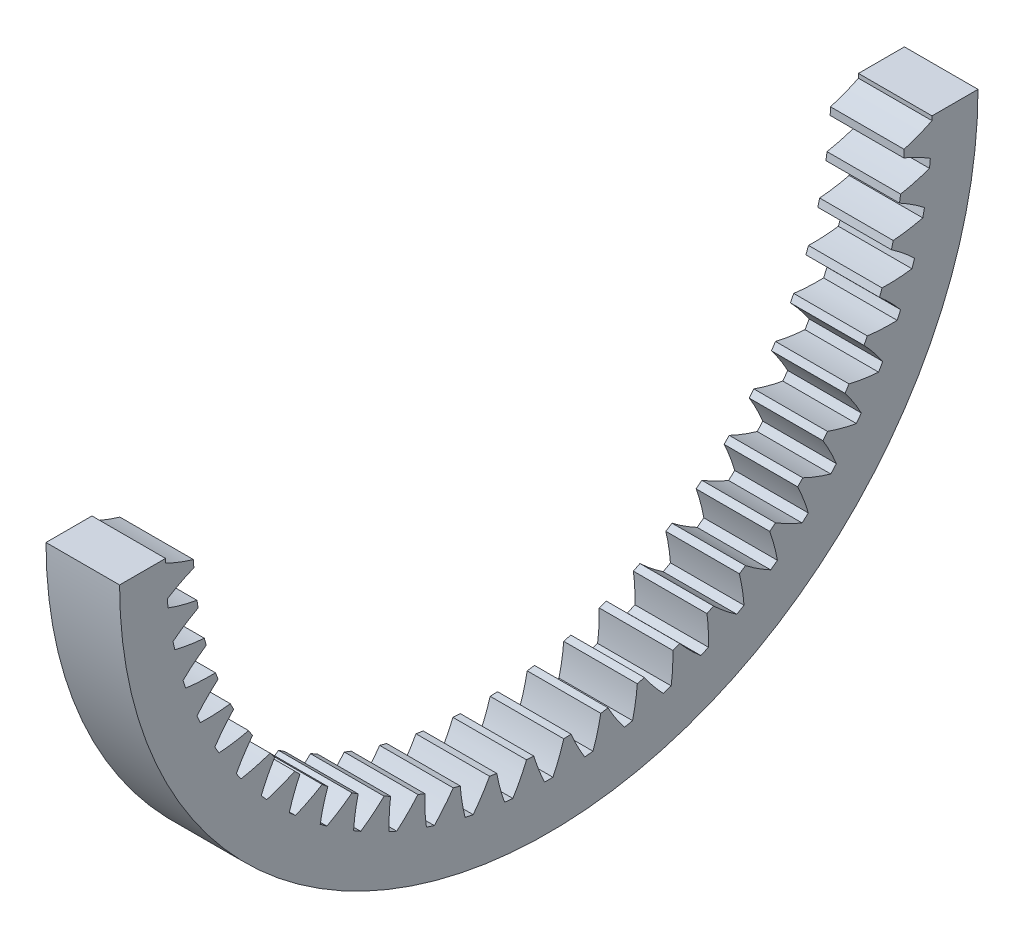
SolidWorks part; units mm, degrees
ref_plane "Plane1" through (0, 0, 0) normal (0, 0, 1) x (1, 0, 0)
ref_plane "Plane2" through (0, 0, 0) normal (0, 1, 0) x (1, 0, 0)
ref_plane "Plane3" through (0, 0, 0) normal (1, 0, 0) x (0, 0, -1)
sketch "HoldingSke" plane through (0, 0, 0) normal (0, 1, 0) x (1, 0, 0)
  line L0 (0, 0) -> (1, -1.7321)
  line L1 (-15, 0) -> (100, 0) construction
  line L2 (0, 0) -> (-2.1039, 2.3779)
  line L3 (0, 0) -> (-11.863, 4.5341)
  line L4 (0, 0) -> (4.318, 7.479)
  line L5 (0, 0) -> (-23.7986, -8.8762)
  line L6 (0, 0) -> (-10.5278, -7.1032)
  line L7 (-2.1039, 2.3779) -> (3.3635, 27.1825)
  line L8 (-76.2, 2.8779) -> (-54.61, 2.8779)
  line L9 (-71.009, 38.7566) -> (-53.1078, 45.2721)
  line L10 (-76.2, 71.12) -> (104.1128, 71.12)
  line L11 (0, 0) -> (-3, 0)
  line L12 (-76.2, 101.6) -> (-76.181, 101.6)
  line L13 (24.9733, 27.94) -> (52.9518, 28.4284)
  line L14 (24.9733, 27.94) -> (24.9743, 27.94)
  line L15 (24.9733, 27.94) -> (100.4006, 29.5858)
  circle A0 centre (0, 0) radius 17.5
  circle A1 centre (0, 0) radius 12.7
  circle A2 centre (0, 0) radius 12.7
  dimension "MHD" = 25.4
  dimension "Hub_dia" = 25.4
  dimension "Diameter" = 35
  dimension "Num_teeth" = 60
  dimension "Pitch" = 2
  dimension "Overall_len" = 25.4
  dimension "Show_teeth" = 60
  dimension "Thickness" = 12.7
  dimension "OAL" = 25.4001
  dimension "T_dim" = 21.59
  dimension "Ap" = 20
  dimension "H" = 19.05
  dimension "Pitch_radius" = 180.3128
  dimension "Width" = 3
  dimension "Backlash" = 0.019
  dimension "Addendum_fac" = 1
  dimension "Dedendum_fac" = 1.25
  dimension "Clearance_fac" = 0.25
  dimension "Dedendum_add" = 0.001
  dimension "Module" = 0.5
sketch "BasProSke" plane through (0, 0, 0) normal (0, 1, 0) x (1, 0, 0)
  line L0 (-10, 0) -> (60, 0) construction
  line L1 (0, 14.5) -> (0, 17.5)
  line L2 (0, 14.5) -> (3, 14.5)
  line L3 (3, 14.5) -> (3, 17.5)
  line L4 (3, 17.5) -> (0, 17.5)
  dimension "Diameter" = 35
  dimension "Thickness" = 3
  dimension "Inside_diameter" = 29
revolve "Base-Revolve" add sketch "BasProSke" angle 360 about L0
sketch "TooCutSke" plane through (0, 0, 0) normal (1, 0, 0) x (0, 0, -1)
  line L3 (0.4402, 14.9935) -> (0.4402, 53.6633) construction
  line L4 (0, 0) -> (0, 59.563) construction
  line L5 (0, 0) -> (-3.576, 68.2339) construction
  line L6 (-6.5816, 12.3583) -> (37.127, 14.649) construction
  circle A0 centre (0, 0) radius 15 construction
  circle A1 centre (0, 0) radius 15.626 construction
  circle A2 centre (0, 0) radius 12.6859 construction
  circle A3 centre (0, 0) radius 14.4746 construction
  arc A4 (0.6175, 14.4614) -> (0.1695, 15.6251) centre (-6.5816, 12.3583) ccw
  arc A5 (0.6175, 14.4614) -> (-0.6175, 14.4614) centre (0, 0) ccw
  arc A6 (0.1695, 15.6251) -> (-0.1695, 15.6251) centre (0, 0) ccw
  arc A7 (-0.1695, 15.6251) -> (-0.6175, 14.4614) centre (6.5816, 12.3583) ccw
  dimension "Pitch_dia" = 30
  dimension "Base_dia" = 25.3717
  dimension "Root_dia" = 31.252
  dimension "Overcut_dia" = 28.9492
  dimension "Flank_rad" = 7.5
  dimension "Half_ang" = 3
  dimension "Half_CT" = 0.4402
extrude "ToothCut" cut sketch "TooCutSke" along normal through all
fillet "Breaks" [suppressed] radius 0.05
fillet "RootFillets" [suppressed] radius 0.126
pattern_circular "TeethCuts" count 60 every 6 about axis through (-10, 0, 0) along (1, 0, 0) of "RootFillets", "Breaks", "ToothCut"
sketch "Croquis1" plane through (3, 0, 0) normal (1, 0, 0) x (0, 0, -1)
  line L0 (0, 0) -> (0, 15)
  line L1 (0, 0) -> (10.6066, -10.6066)
  line L3 (-10.6066, -10.6066) -> (0, 0)
  circle A0 centre (0, 0) radius 15
  dimension "D1" = 30
  dimension "D2" = 135
  dimension "D3" = 135
sketch "Croquis2" plane through (0, 0, 0) normal (1, 0, 0) x (0, 0, -1)
  line L1 (-21.2132, 0) -> (20.1533, 0)
  line L2 (-21.2132, 0) -> (-21.2132, 18.9733)
  line L3 (-21.2132, 18.9733) -> (20.1533, 18.9733)
  line L4 (20.1533, 0) -> (20.1533, 18.9733)
extrude "Cortar-Extruir1" cut sketch "Croquis2" along normal through all
equation "' \"Module@HoldingSke\" = 6.35"
equation "' \"Num_teeth@HoldingSke\" = 24"
equation "' \"Ap@HoldingSke\" =  14.5"
equation "' \"Ap@HoldingSke\" = 14.5"
equation "' \"Width@HoldingSke\" = 12"
equation "' \"Diameter@HoldingSke\" = 8 * 25.4"
equation "' \"Show_teeth@HoldingSke\" = 100"
equation "' \"Backlash@HoldingSke\" = 0.009 * 25.4"
equation "' \"Addendum_fac@HoldingSke\" = 1.0"
equation "' \"Dedendum_fac@HoldingSke\" = 1.25"
equation "' \"Dedendum_add@HoldingSke\" = 0.00005 * 25.4"
equation "' \"Clearance_fac@HoldingSke\" = 0.25"
equation "\"Pitch@HoldingSke\" = 1 / \"Module@HoldingSke\" "
equation "\"Overcut_dia@TooCutSke\" = (\"Num_teeth@HoldingSke\" - 2 * \"Addendum_fac@HoldingSke\") / \"Pitch@HoldingSke\" - 0.002 * 25.4"
equation "\"Pitch_dia@TooCutSke\" = \"Num_teeth@HoldingSke\" / \"Pitch@HoldingSke\""
equation "\"Base_dia@TooCutSke\" = \"Num_teeth@HoldingSke\" / \"Pitch@HoldingSke\" * cos((\"Ap@HoldingSke\"  * 3.14159265 / 180)) * 0.90"
equation "\"Root_dia@TooCutSke\" = \"Num_teeth@HoldingSke\"  / \"Pitch@HoldingSke\" + 2 *  \"Dedendum_fac@HoldingSke\"/ \"Pitch@HoldingSke\" + \"Dedendum_add@HoldingSke\" * 2"
equation "\"Half_ang@TooCutSke\" = 180 / \"Num_teeth@HoldingSke\""
equation "\"Half_CT@TooCutSke\" = \"Num_teeth@HoldingSke\" / \"Pitch@HoldingSke\" * sin((3.14159265 / 2 / \"Num_teeth@HoldingSke\")) / 2 + 10 * \"Backlash@HoldingSke\" / 4"
equation "\"Flank_rad@TooCutSke\" = \"Num_teeth@HoldingSke\" / \"Pitch@HoldingSke\" / 4"
equation "\"Radius@RootFillets\"= \"Clearance_fac@HoldingSke\" / \"Pitch@HoldingSke\" + \"Dedendum_add@HoldingSke\""
equation "\"Break_rad@Breaks\" = 0.02 / \"Pitch@HoldingSke\" * 5"
equation "\"Num_teeth@TeethCuts\" = int( \"Show_teeth@HoldingSke\" ) + 1"
equation "\"Num_teeth@TeethCuts\" = ((sgn( \"Num_teeth@TeethCuts\" - \"Num_teeth@HoldingSke\" )-1)*( \"Num_teeth@TeethCuts\" - \"Num_teeth@HoldingSke\" ))/-2+ \"Num_teeth@HoldingSke\""
equation "\"Num_teeth@TeethCuts\" = ((sgn( \"Num_teeth@TeethCuts\" - 2.0)+1)*( \"Num_teeth@TeethCuts\" - 2.0))/2 +2.0"
equation "\"Angle@TeethCuts\" = 360.0 / \"Num_teeth@HoldingSke\""
equation "\"Diameter@BasProSke\" = \"Num_teeth@HoldingSke\"  / \"Pitch@HoldingSke\" + 2 *  \"Dedendum_fac@HoldingSke\"/ \"Pitch@HoldingSke\" + \"Dedendum_add@HoldingSke\" * 2 + 0.002 * 25.4"
equation "\"Diameter@BasProSke\" = ((sgn( \"Diameter@BasProSke\"  - \"Diameter@HoldingSke\" )+1)*( \"Diameter@BasProSke\"  - \"Diameter@HoldingSke\" ))/2 + \"Diameter@HoldingSke\""
equation "\"Inside_diameter@BasProSke\" =  (\"Num_teeth@HoldingSke\" - 2 * \"Addendum_fac@HoldingSke\") / \"Pitch@HoldingSke\" "
equation "\"Thickness@BasProSke\"  = \"Width@HoldingSke\""
